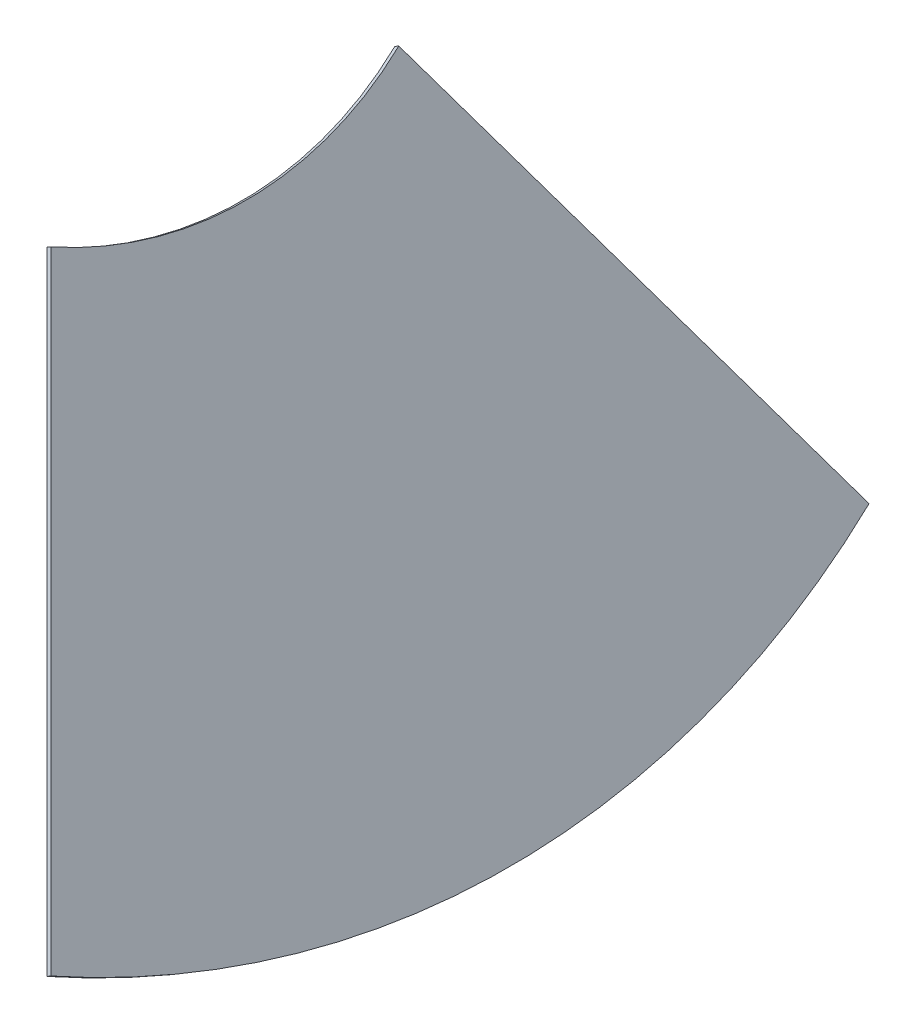
SolidWorks part; units mm, degrees
ref_plane "Front Plane" through (0, 0, 0) normal (0, 0, 1) x (1, 0, 0)
ref_plane "Top Plane" through (0, 0, 0) normal (0, 1, 0) x (1, 0, 0)
ref_plane "Right Plane" through (0, 0, 0) normal (1, 0, 0) x (0, 0, -1)
sketch "Sketch2" plane through (18.3047, 56.1039, 84.5047) normal (-0.86, -0.5103, 0) x (-0.3618, 0.6097, 0.7052)
  line L38 (-158.2642, -288.9643) -> (-155.2466, -289.9517) construction
  line L40 (-88.3532, -75.3036) -> (-85.3356, -76.291) construction
  line L41 (-64.9698, -3.8395) -> (-158.2642, -288.9643) construction
  line L42 (-155.2466, -289.9517) -> (-61.9522, -4.8268) construction
  line L43 (-409.9628, -33.8767) -> (-408.9915, -36.8995) construction
  line L44 (-195.9332, 34.8966) -> (-194.962, 31.8738) construction
  line L45 (-124.3458, 57.8995) -> (-409.9628, -33.8767) construction
  line L46 (-408.9915, -36.8995) -> (-123.3745, 54.8768) construction
  line L47 (-158.2642, -288.9643) -> (-88.3532, -75.3036)
  line L48 (-408.9915, -36.8995) -> (-194.962, 31.8738)
  arc A3 (-88.3532, -75.3036) -> (-194.962, 31.8738) centre (-36.638, 82.7475) cw
  arc A4 (-158.2642, -288.9643) -> (-408.9915, -36.8995) centre (-36.638, 82.7475) cw
  dimension "D1" = 55.1924
surface "Surface-Plane1" sketch "Sketch2"
thicken "Thicken1" thickness 1 thickness side both sides parameters "D1"=1
